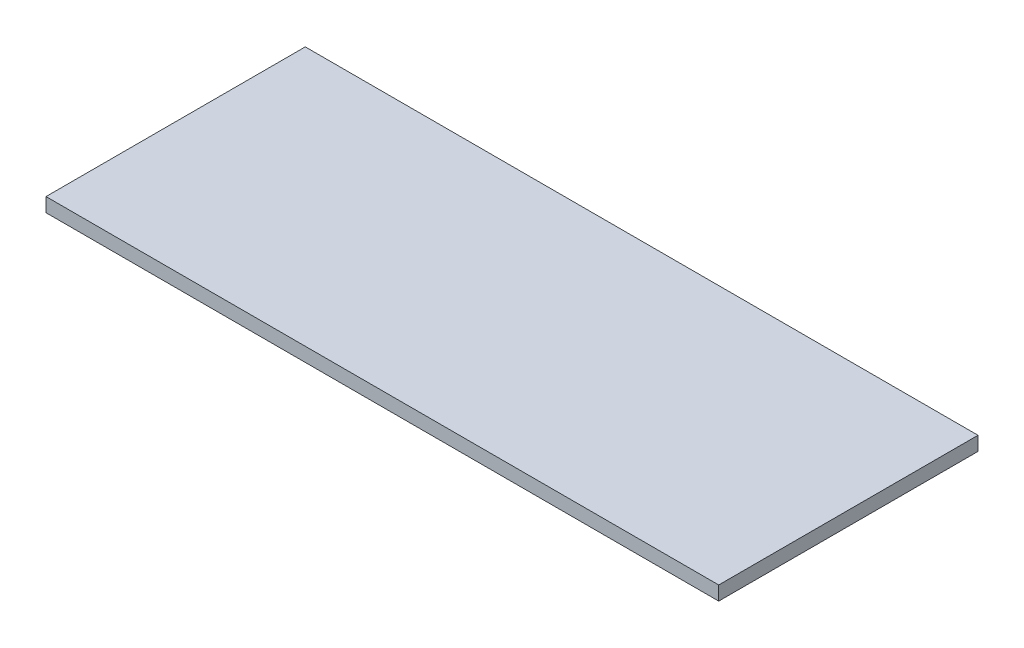
SolidWorks part; units mm, degrees
ref_plane "Front Plane" through (0, 0, 0) normal (0, 0, 1) x (1, 0, 0)
ref_plane "Top Plane" through (0, 0, 0) normal (0, 1, 0) x (1, 0, 0)
ref_plane "Right Plane" through (0, 0, 0) normal (1, 0, 0) x (0, 0, -1)
sketch "Sketch1" plane through (0, 0, 0) normal (0, 1, 0) x (1, 0, 0)
  line L0 (-314.325, 266.7) -> (-314.325, -12.7) construction
  line L5 (-304.8, 0) -> (304.8, 0)
  line L6 (-304.8, 0) -> (-304.8, 234.95)
  line L7 (-304.8, 234.95) -> (304.8, 234.95)
  line L8 (304.8, 0) -> (304.8, 234.95)
  line L9 (-304.8, 0) -> (304.8, 234.95) construction
  line L10 (-304.8, 234.95) -> (304.8, 0) construction
  line L11 (314.325, 266.7) -> (-144.4737, 266.7) construction
  point P0 (0, 117.475)
  dimension "D1" = 9.525
  dimension "D2" = 31.75
extrude "Boss-Extrude1" add sketch "Sketch1" along normal blind 12.7
